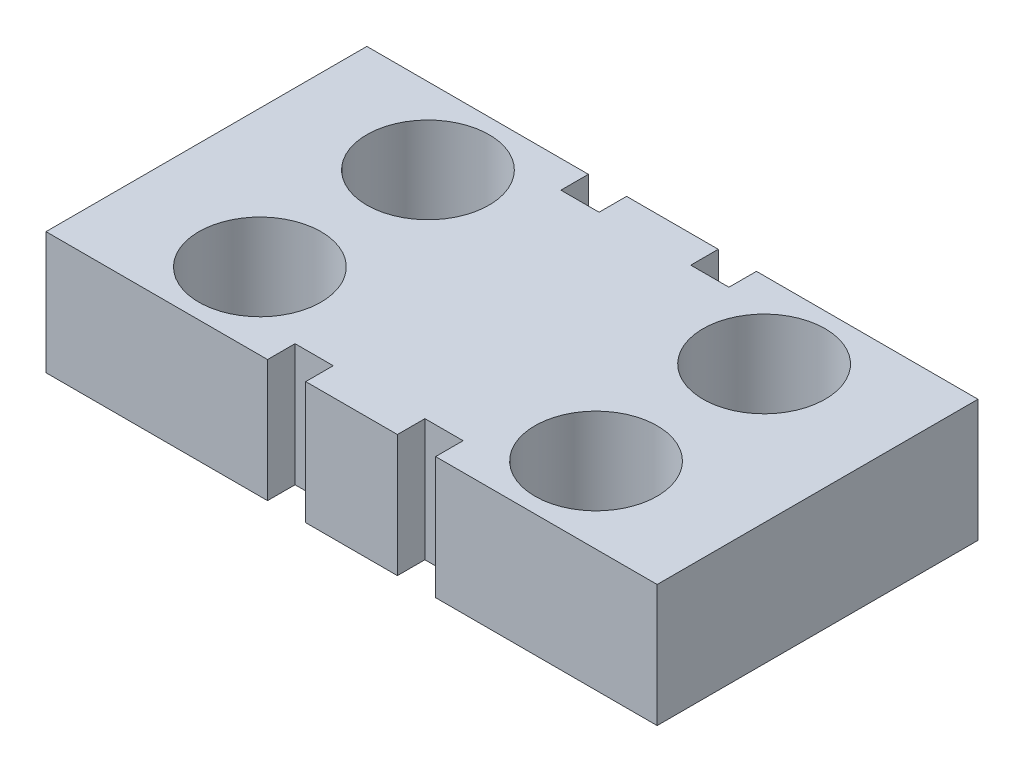
SolidWorks part; units mm, degrees
ref_plane "Płaszczyzna przednia" through (0, 0, 0) normal (0, 0, 1) x (1, 0, 0)
ref_plane "Płaszczyzna górna" through (0, 0, 0) normal (0, 1, 0) x (1, 0, 0)
ref_plane "Płaszczyzna prawa" through (0, 0, 0) normal (1, 0, 0) x (0, 0, -1)
sketch "Sketch1" plane through (0, 0, 0) normal (0, 1, 0) x (1, 0, 0)
  line L1 (-40, 21) -> (0, 21)
  line L2 (-40, 21) -> (-40, 0)
  line L3 (-40, 0) -> (0, 0)
  line L4 (0, 21) -> (0, 0)
  dimension "D1" = 40
  dimension "D2" = 21
extrude "Boss-Extrude1" add sketch "Sketch1" along normal blind 8
sketch "Sketch2" plane through (0, 8, 0) normal (0, 1, 0) x (1, 0, 0)
  line L0 (-40, 10.5) -> (-9.7076, 10.5) construction
  line L1 (-20, 21) -> (-20, -8.7627) construction
  line L2 (-40, 21) -> (-40, 0) construction
  line L3 (0, 21) -> (-40, 21) construction
  circle A0 centre (-31, 16) radius 4
  circle A1 centre (-31, 5) radius 4
  circle A2 centre (-9, 5) radius 4
  circle A3 centre (-9, 16) radius 4
  dimension "D1" = 8
  dimension "D2" = 9
  dimension "D3" = 5
extrude "Cut-Extrude1" cut sketch "Sketch2" against normal blind 7
sketch "Sketch3" plane through (0, 0, 0) normal (0, -1, 0) x (1, 0, 0)
  line L0 (-40, 0) -> (0, -21) construction
  circle A0 centre (-20, -10.5) radius 2.5
  point P3 (-20, -10.5)
  dimension "D1" = 5
extrude "Cut-Extrude2" cut sketch "Sketch3" against normal blind 5
sketch "Sketch4" plane through (0, 0, 0) normal (0, -1, 0) x (1, 0, 0)
  line L0 (-20, 0) -> (-20, -21) construction
  line L1 (-40, -10.5) -> (0, -10.5) construction
  line L2 (-40, 0) -> (0, 0) construction
  line L3 (0, -21) -> (-40, -21) construction
  line L4 (-40, -21) -> (-40, 0) construction
  line L5 (0, 0) -> (0, -21) construction
  line L6 (-14.5, -1.8) -> (-17, -1.8)
  line L7 (-25.5, 0) -> (-23, 0)
  line L8 (-25.5, 0) -> (-25.5, -1.8)
  line L9 (-25.5, -1.8) -> (-23, -1.8)
  line L10 (-23, 0) -> (-23, -1.8)
  line L11 (-17, 0) -> (-17, -1.8)
  line L12 (-14.5, 0) -> (-17, 0)
  line L13 (-14.5, 0) -> (-14.5, -1.8)
  line L14 (-14.5, -21) -> (-14.5, -19.2)
  line L15 (-14.5, -21) -> (-17, -21)
  line L16 (-17, -21) -> (-17, -19.2)
  line L17 (-14.5, -19.2) -> (-17, -19.2)
  line L18 (-25.5, -19.2) -> (-23, -19.2)
  line L19 (-23, -21) -> (-23, -19.2)
  line L20 (-25.5, -21) -> (-23, -21)
  line L21 (-25.5, -21) -> (-25.5, -19.2)
  dimension "D1" = 2.5
  dimension "D2" = 1.8
  dimension "D3" = 3
extrude "Cut-Extrude3" cut sketch "Sketch4" against normal blind 15
